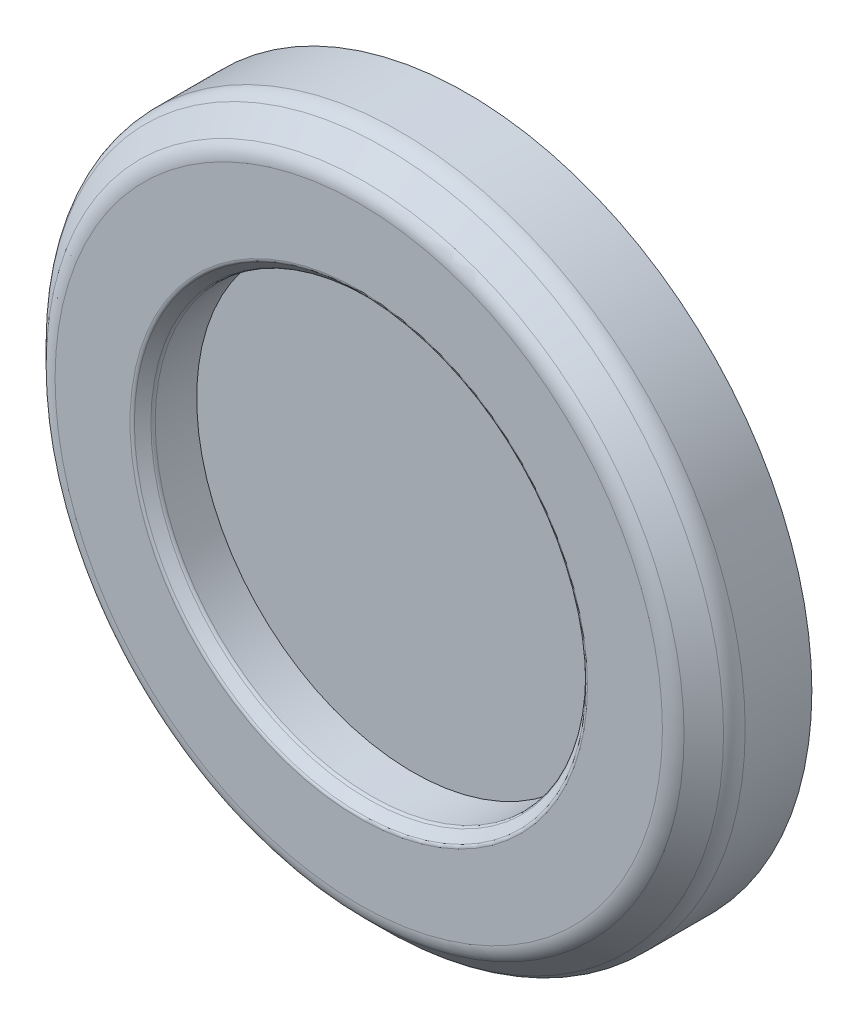
SolidWorks part; units mm, degrees
material "moto_black"
ref_plane "Front Plane" through (0, 0, 0) normal (0, 0, 1) x (1, 0, 0)
ref_plane "Top Plane" through (0, 0, 0) normal (0, 1, 0) x (1, 0, 0)
ref_plane "Right Plane" through (0, 0, 0) normal (1, 0, 0) x (0, 0, -1)
sketch "Sketch1" plane through (0, 0, 0) normal (0, 0, 1) x (1, 0, 0)
  circle A0 centre (0, 0) radius 31.93
  dimension "D1" = 63.86
extrude "Boss-Extrude1" add sketch "Sketch1" along normal blind 10
chamfer "Chamfer1" distance 3 angle 45 1 edges at (31.93, 0, 10)
fillet "Fillet1" radius 2 2 edges at (31.93, 0, 7) (28.93, 0, 10)
sketch "Sketch2" plane through (0, 0, 10) normal (0, 0, 1) x (1, 0, 0)
  circle A0 centre (0, 0) radius 20
  dimension "D1" = 40
extrude "Cut-Extrude1" cut sketch "Sketch2" against normal blind 5
chamfer "Chamfer2" distance 1 angle 45 1 edges at (20, 0, 10)
fillet "Fillet2" radius 0.4 2 edges at (20, 0, 9) (21, 0, 10)
